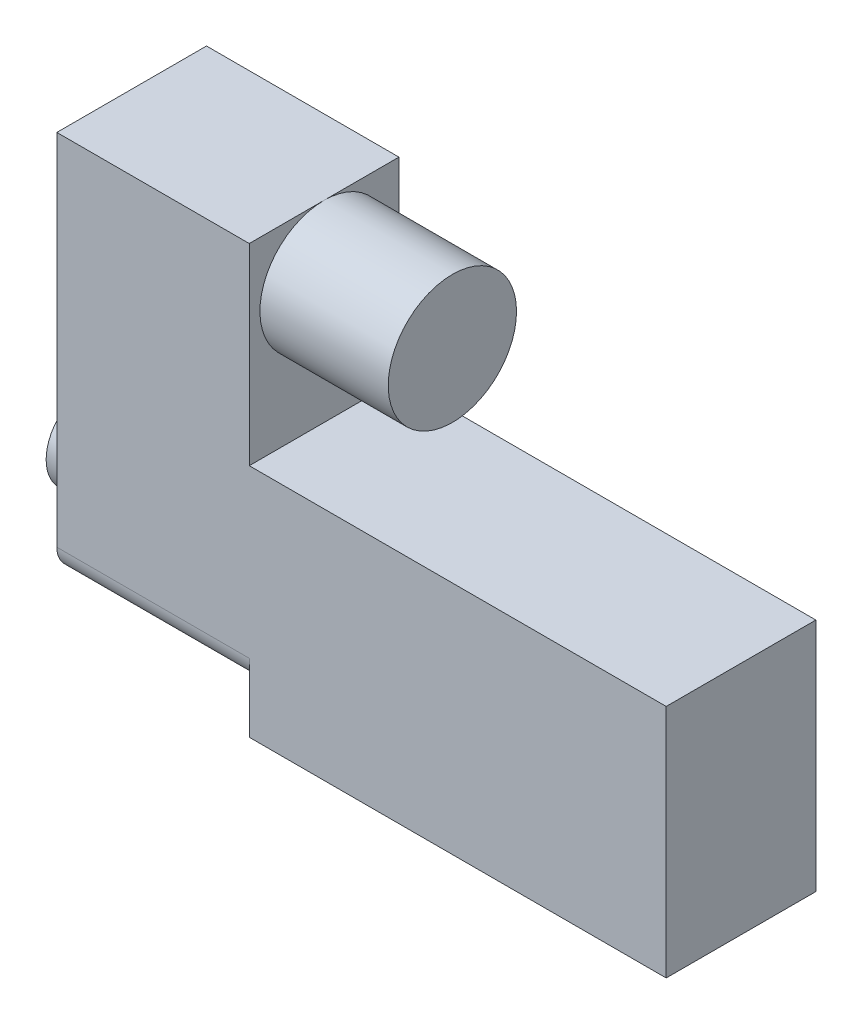
SolidWorks part; units mm, degrees
ref_plane "Front Plane" through (0, 0, 0) normal (0, 0, 1) x (1, 0, 0)
ref_plane "Top Plane" through (0, 0, 0) normal (0, 1, 0) x (1, 0, 0)
ref_plane "Right Plane" through (0, 0, 0) normal (1, 0, 0) x (0, 0, -1)
sketch "Sketch1" plane through (0, 0, 0) normal (0, 1, 0) x (1, 0, 0)
  line L1 (0, 0) -> (61.9125, 0)
  line L2 (0, 0) -> (0, 22.225)
  line L3 (0, 22.225) -> (61.9125, 22.225)
  line L4 (61.9125, 0) -> (61.9125, 22.225)
  dimension "D1" = 61.9125
  dimension "D2" = 22.225
extrude "Boss-Extrude1" add sketch "Sketch1" along normal blind 34.925
sketch "Sketch2" plane through (0, 0, 0) normal (-1, 0, 0) x (0, 0, 1)
  line L0 (0, 34.925) -> (0, 0) construction
  line L1 (-22.225, 34.925) -> (0, 34.925)
  line L2 (-22.225, 34.925) -> (-22.225, 6.35)
  line L3 (-22.225, 6.35) -> (0, 6.35)
  line L4 (0, 34.925) -> (0, 6.35)
  dimension "D1" = 28.575
extrude "Boss-Extrude2" add sketch "Sketch2" along normal blind 28.575
sketch "Sketch3" plane through (0, 34.925, 0) normal (0, 1, 0) x (1, 0, 0)
  line L0 (-28.575, 0) -> (61.9125, 0) construction
  line L1 (-28.575, 22.225) -> (0, 22.225)
  line L2 (-28.575, 22.225) -> (-28.575, 0)
  line L3 (-28.575, 0) -> (0, 0)
  line L4 (0, 22.225) -> (0, 0)
  dimension "D1" = 28.575
extrude "Boss-Extrude3" add sketch "Sketch3" along normal blind 28.575
sketch "Sketch4" plane through (0, 0, 0) normal (1, 0, 0) x (0, 0, -1)
  line L1 (11.1125, 63.5) -> (11.1125, 34.925) construction
  line L2 (0, 63.5) -> (22.225, 63.5) construction
  line L3 (0, 34.925) -> (22.225, 34.925) construction
  circle A0 centre (11.1125, 53.975) radius 9.525
  dimension "D1" = 19.05
extrude "Boss-Extrude4" add sketch "Sketch4" along normal blind 19.05
sketch "Sketch5" plane through (-28.575, 0, 0) normal (-1, 0, 0) x (0, 0, 1)
  line L0 (-11.1125, 63.5) -> (-11.1125, 6.35) construction
  line L1 (-22.225, 63.5) -> (0, 63.5) construction
  line L2 (-22.225, 6.35) -> (0, 6.35) construction
  circle A0 centre (-11.1125, 15.875) radius 6.35
  dimension "D1" = 12.7
  dimension "D2" = 9.525
extrude "Boss-Extrude5" add sketch "Sketch5" along normal blind 6.35
fillet "Fillet1" radius 3.81 2 edges
